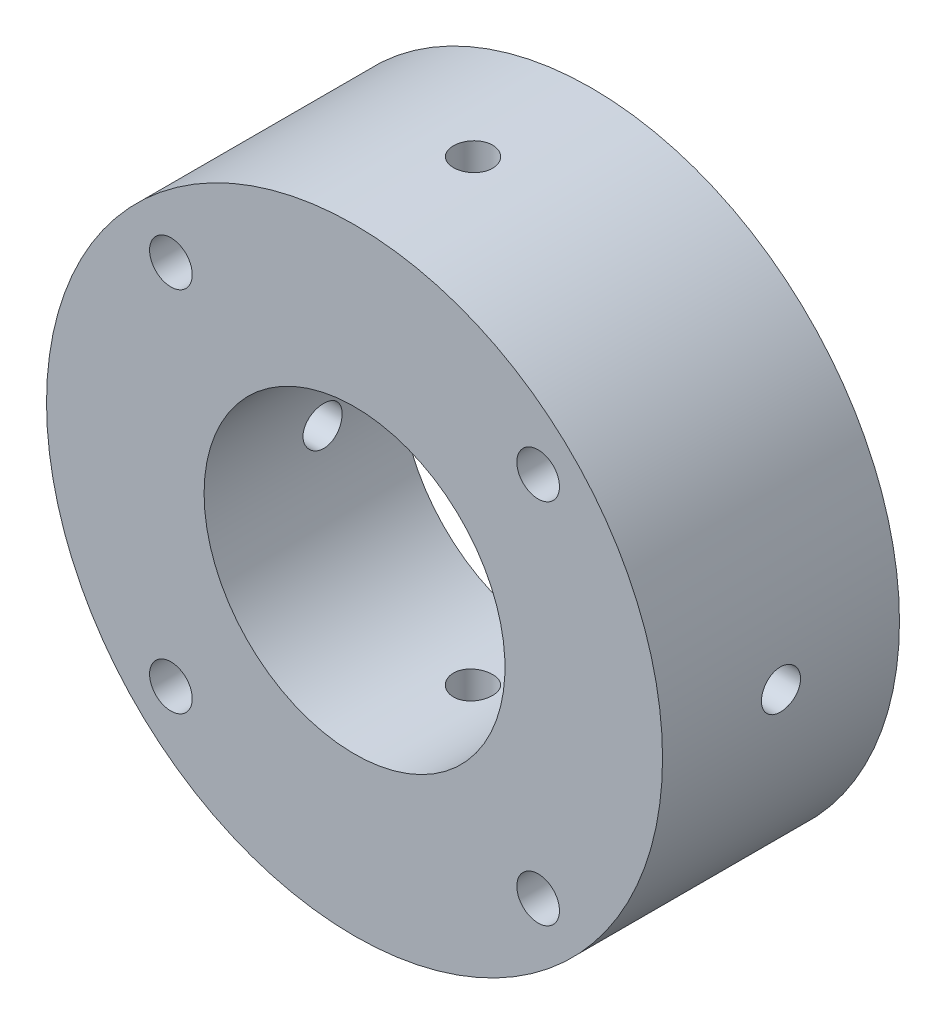
SolidWorks part; units mm, degrees
material "6061 Alloy"
ref_plane "Front" through (0, 0, 0) normal (0, 0, 1) x (1, 0, 0)
ref_plane "Top" through (0, 0, 0) normal (0, 1, 0) x (1, 0, 0)
ref_plane "Right" through (0, 0, 0) normal (1, 0, 0) x (0, 0, -1)
ref_plane "Plane1" through (0, 0, 0) normal (0, -1, 0) x (1, 0, 0)
sketch "Sketch1" plane through (0, 0, 0) normal (0, -1, 0) x (1, 0, 0)
  line L0 (26, 20) -> (0, 20)
  line L1 (0, 20) -> (0, 0)
  line L2 (0, 0) -> (26, 0)
  line L3 (26, 0) -> (26, 20)
  line L4 (0, 20) -> (0, 0) construction
revolve "Revolve1" add sketch "Sketch1" angle 360 about L4
hole_wizard "M3x0.5 Tapped Hole1" positions "Sketch3" profile "Sketch2" tap size "M3x0.5" standard "ANSI Metric"
sketch "Sketch3" plane through (0, 0, 0) normal (0, 0, -1) x (-1, 0, 0)
  point P0 (-22.7762, 3.201)
sketch "Sketch2" plane through (22.7762, 3.201, 0) normal (1, 0, 0) x (0, 1, 0)
  line L0 (0, 0) -> (0, 6.7511)
  line L1 (0, 6.7511) -> (1.25, 6)
  line L2 (1.25, 6) -> (1.25, 0)
  line L5 (1.25, 0) -> (0, 0)
  line L10 (0, 6.7511) -> (-1.25, 6) construction
  line L11 (0, -6.35) -> (0, 107.95) construction
  dimension "Tap Drill Dia." = 2.5
  dimension "Tap Drill Depth" = 6
  dimension "Drill Angle" = 118
hole_wizard "Hole1" positions "Sketch5" profile "Sketch4" legacy
sketch "Sketch5" plane through (0, 0, 0) normal (0, 0, -1) x (-1, 0, 0)
  point P0 (0, 0)
sketch "Sketch4" plane through (0, 0, 0) normal (1, 0, 0) x (0, 1, 0)
  line L0 (0, 0) -> (0, 20)
  line L1 (0, 20) -> (12.7, 20)
  line L2 (12.7, 20) -> (12.7, 3.4)
  line L3 (12.7, 3.4) -> (20, 3.4)
  line L4 (20, 3.4) -> (20, 0)
  line L5 (20, 0) -> (0, 0)
  line L6 (0, 110) -> (0, -10) construction
  dimension "Diameter" = 25.4
  dimension "Depth" = 20
  dimension "C-Bore Diameter" = 40
  dimension "C-Bore Depth" = 3.4
hole_wizard "M4x0.7 Tapped Hole1" positions "3DSketch1" profile "Sketch6" tap size "M4x0.7" standard "ANSI Metric" end condition through all
sketch3d "3DSketch1"
  point P0 (26, 0, 10)
sketch "Sketch6" plane through (26, 0, 10) normal (0, 1, 0) x (0, 0, -1)
  line L0 (0, 0) -> (0, 52)
  line L1 (0, 52) -> (1.65, 52)
  line L2 (1.65, 52) -> (1.65, 0)
  line L5 (1.65, 0) -> (0, 0)
  line L11 (0, -6.35) -> (0, 107.95) construction
  dimension "Thru Tap Drill Dia." = 3.3
  dimension "Thru Tap Drill Depth" = 52
ref_plane "Plane2" through (0, 12.5924, 0) normal (0, -1, 0) x (-1, 0, 0)
hole_wizard "M4x0.7 Tapped Hole2" positions "Sketch8" profile "Sketch7" tap size "M4x0.7" standard "ANSI Metric"
sketch "Sketch8" plane through (0, 12.5924, 0) normal (0, -1, 0) x (-1, 0, 0)
  point P0 (0, -10)
sketch "Sketch7" plane through (0, 12.5924, 10) normal (1, 0, 0) x (0, 0, -1)
  line L0 (0, 0) -> (0, 13.4076)
  line L1 (0, 13.4076) -> (1.65, 13.4076)
  line L2 (1.65, 13.4076) -> (1.65, 0)
  line L5 (1.65, 0) -> (0, 0)
  line L11 (0, -6.35) -> (0, 107.95) construction
  dimension "Thru Tap Drill Dia." = 3.3
  dimension "Thru Tap Drill Depth" = 13.4076
ref_plane "Plane3" through (0, -12.5924, 0) normal (0, 1, 0) x (1, 0, 0)
hole_wizard "#4 Clearance Hole3" positions "Sketch10" profile "Sketch9" hole size "#4" standard "ANSI Inch"
sketch "Sketch10" plane through (0, -12.5924, 0) normal (0, 1, 0) x (1, 0, 0)
  point P0 (0, -10)
sketch "Sketch9" plane through (0, -12.5924, 10) normal (1, 0, 0) x (0, 0, 1)
  line L0 (0, 0) -> (0, 13.4076)
  line L1 (0, 13.4076) -> (1.65, 13.4076)
  line L2 (1.65, 13.4076) -> (1.65, 0)
  line L5 (1.65, 0) -> (0, 0)
  line L11 (0, -6.35) -> (0, 107.95) construction
  dimension "Thru Hole Dia." = 3.3
  dimension "Thru Hole Depth" = 13.4076
hole_wizard "CBORE for M3 SHCS1" positions "Sketch12" profile "Sketch11" counterbore size "M3" standard "ANSI Metric" end condition through all
sketch "Sketch12" plane through (0, 0, 0) normal (0, 0, -1) x (-1, 0, 0)
  point P0 (-15.5, -15.5)
  point P1 (-15.5, 15.5)
  point P2 (15.5, 15.5)
  point P3 (15.5, -15.5)
sketch "Sketch11" plane through (15.5, -15.5, 0) normal (1, 0, 0) x (0, 1, 0)
  line L0 (0, 0) -> (0, 20)
  line L1 (0, 20) -> (1.8, 20)
  line L3 (1.8, 20) -> (1.8, 7.5)
  line L4 (1.8, 7.5) -> (3.25, 7.5)
  line L5 (3.25, 7.5) -> (3.25, 0)
  line L7 (3.25, 0) -> (0, 0)
  line L11 (0, -6.35) -> (0, 107.95) construction
  dimension "Thru Hole Dia." = 3.6
  dimension "Thru Hole Depth" = 20
  dimension "C'Bore Dia." = 6.5
  dimension "C'Bore Depth" = 7.5
